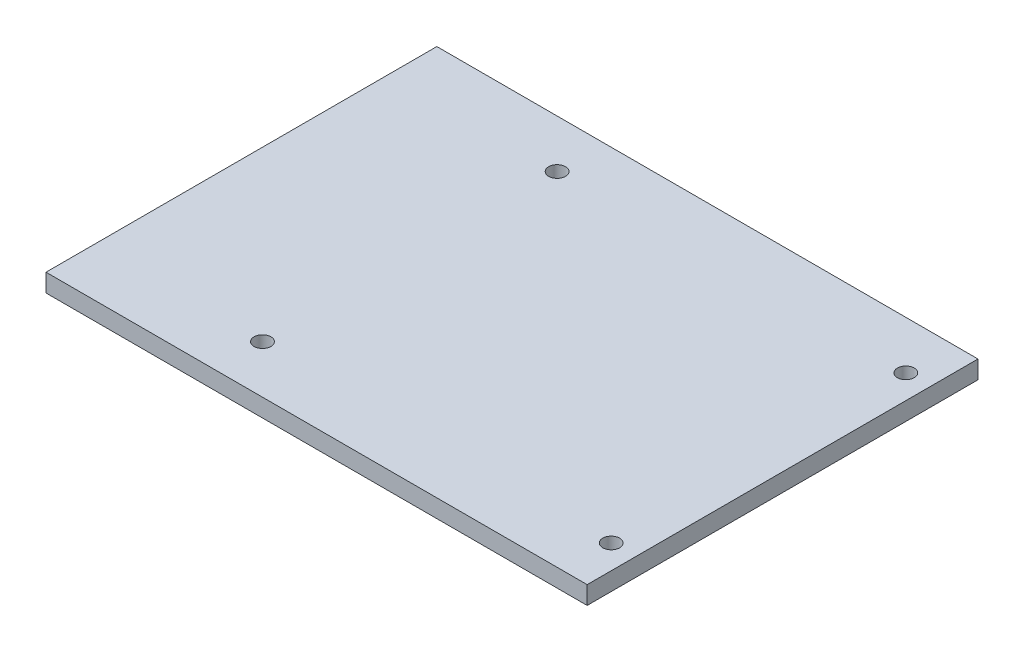
SolidWorks part; units mm, degrees
ref_plane "前视基准面" through (0, 0, 0) normal (0, 0, 1) x (1, 0, 0)
ref_plane "上视基准面" through (0, 0, 0) normal (0, 1, 0) x (1, 0, 0)
ref_plane "右视基准面" through (0, 0, 0) normal (1, 0, 0) x (0, 0, -1)
other "Configuration Table"
sketch "草图1" plane through (0, 0, 0) normal (0, 1, 0) x (1, 0, 0)
  line L1 (-45, -32.5) -> (45, -32.5)
  line L2 (-45, -32.5) -> (-45, 32.5)
  line L3 (-45, 32.5) -> (45, 32.5)
  line L4 (45, -32.5) -> (45, 32.5)
  line L5 (-45, -32.5) -> (45, 32.5) construction
  line L6 (-45, 32.5) -> (45, -32.5) construction
  point P0 (0, 0)
  dimension "D1" = 90
  dimension "D2" = 65
extrude "凸台-拉伸1" add sketch "草图1" along normal blind 3
sketch "草图2" plane through (0, 3, 0) normal (0, 1, 0) x (1, 0, 0)
  line L1 (41, -24.5) -> (-17, -24.5) construction
  line L2 (41, -24.5) -> (41, 24.5) construction
  line L3 (41, 24.5) -> (-17, 24.5) construction
  line L4 (-17, -24.5) -> (-17, 24.5) construction
  line L5 (41, -24.5) -> (-17, 24.5) construction
  line L6 (41, 24.5) -> (-17, -24.5) construction
  circle A0 centre (41, 24.5) radius 1.4
  circle A1 centre (-17, 24.5) radius 1.4
  circle A2 centre (-17, -24.5) radius 1.4
  circle A3 centre (41, -24.5) radius 1.4
  point P0 (12, 0)
  dimension "D4" = 2.8
  dimension "D1" = 58
  dimension "D2" = 49
  dimension "D3" = 12
extrude "切除-拉伸1" cut sketch "草图2" against normal blind 3
